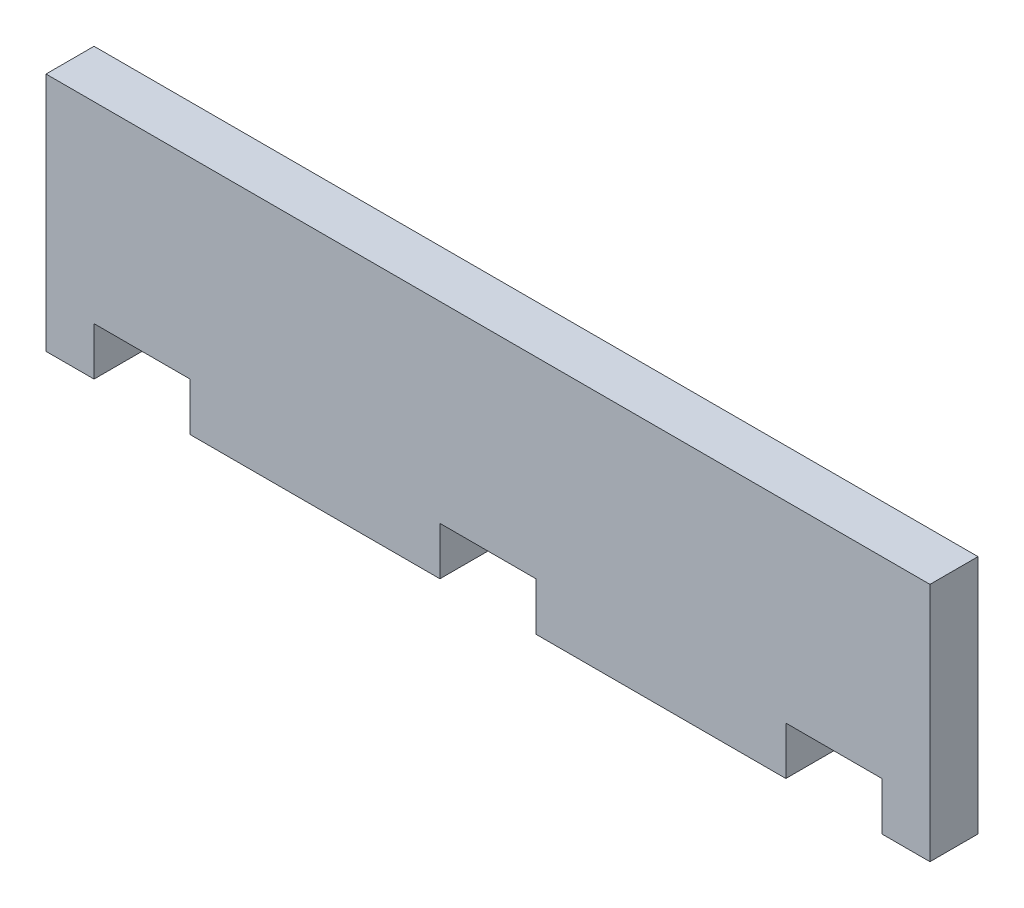
SolidWorks part; units mm, degrees
ref_plane "Front Plane" through (0, 0, 0) normal (0, 0, 1) x (1, 0, 0)
ref_plane "Top Plane" through (0, 0, 0) normal (0, 1, 0) x (1, 0, 0)
ref_plane "Right Plane" through (0, 0, 0) normal (1, 0, 0) x (0, 0, -1)
sketch "Sketch1" plane through (0, 0, 0) normal (0, 0, 1) x (1, 0, 0)
  line L1 (0, 0) -> (116.84, 0)
  line L2 (0, 0) -> (0, 31.75)
  line L3 (0, 31.75) -> (116.84, 31.75)
  line L4 (116.84, 0) -> (116.84, 31.75)
  dimension "D1" = 116.84
  dimension "D2" = 31.75
extrude "Boss-Extrude1" add sketch "Sketch1" along normal blind 6.35
sketch "Sketch2" plane through (0, 0, 6.35) normal (0, 0, 1) x (1, 0, 0)
  line L0 (0, 0) -> (116.84, 0) construction
  line L1 (6.35, 0) -> (19.05, 0)
  line L2 (6.35, 0) -> (6.35, 6.35)
  line L3 (6.35, 6.35) -> (19.05, 6.35)
  line L4 (19.05, 0) -> (19.05, 6.35)
  line L5 (0, 31.75) -> (0, 0) construction
  line L6 (58.42, 0) -> (58.42, 31.75) construction
  line L7 (116.84, 31.75) -> (0, 31.75) construction
  line L8 (110.49, 0) -> (110.49, 6.35)
  line L9 (110.49, 6.35) -> (97.79, 6.35)
  line L10 (97.79, 0) -> (97.79, 6.35)
  line L11 (110.49, 0) -> (97.79, 0)
  line L13 (52.07, 0) -> (64.77, 0)
  line L14 (52.07, 0) -> (52.07, 6.35)
  line L15 (52.07, 6.35) -> (64.77, 6.35)
  line L16 (64.77, 0) -> (64.77, 6.35)
  dimension "D1" = 12.7
  dimension "D2" = 6.35
  dimension "D3" = 6.35
  dimension "D4" = 12.7
  dimension "D5" = 6.35
  dimension "D6" = 6.35
extrude "Cut-Extrude1" cut sketch "Sketch2" against normal blind 6.35
